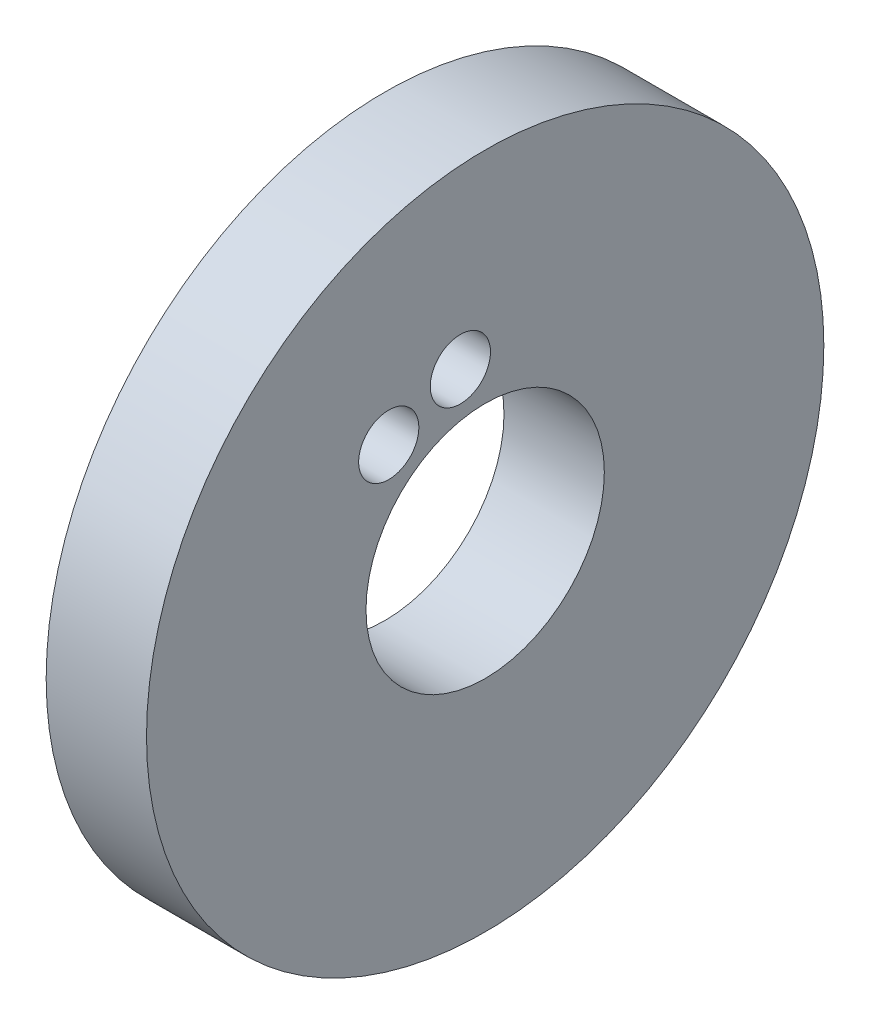
SolidWorks part; units mm, degrees
material "Alumina"
ref_plane "Front Plane" through (0, 0, 0) normal (0, 0, 1) x (1, 0, 0)
ref_plane "Top Plane" through (0, 0, 0) normal (0, 1, 0) x (1, 0, 0)
ref_plane "Right Plane" through (0, 0, 0) normal (1, 0, 0) x (0, 0, -1)
sketch "Axial profile (mm)" plane through (0, 0, 0) normal (0, 0, 1) x (1, 0, 0)
  line L0 (-110, 0) -> (75, 0) construction
  line L1 (135.7, 9.5) -> (143.7, 9.5)
  line L2 (143.7, 9.5) -> (143.7, 27)
  line L3 (143.7, 27) -> (135.7, 27)
  line L4 (135.7, 27) -> (135.7, 9.5)
revolve "Full revolution" add sketch "Axial profile (mm)" angle 360 about L0
sketch "Sketch2" plane through (0, 0, 0) normal (1, 0, 0) x (0, 0, -1)
  circle A0 centre (-1.9774, 12.8487) radius 2.4
  circle A1 centre (-7.6872, 10.4836) radius 2.4
extrude "Axial holes" cut sketch "Sketch2" against normal through all and the other way through all
